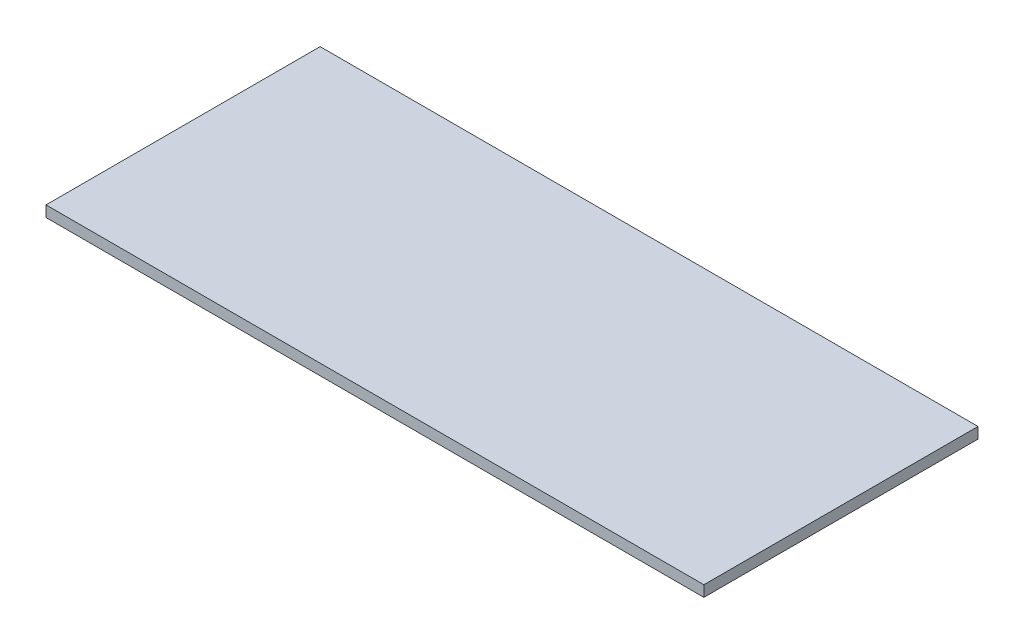
SolidWorks part; units mm, degrees
ref_plane "Front" through (0, 0, 0) normal (0, 0, 1) x (1, 0, 0)
ref_plane "Top" through (0, 0, 0) normal (0, 1, 0) x (1, 0, 0)
ref_plane "Right" through (0, 0, 0) normal (1, 0, 0) x (0, 0, -1)
sketch "Sketch1" plane through (0, 0, 0) normal (0, 1, 0) x (1, 0, 0)
  line L1 (-300, 125) -> (300, 125)
  line L2 (-300, 125) -> (-300, -125)
  line L3 (-300, -125) -> (300, -125)
  line L4 (300, 125) -> (300, -125)
  line L5 (-300, 125) -> (300, -125) construction
  line L6 (-300, -125) -> (300, 125) construction
  point P0 (0, 0)
  dimension "D1" = 250
  dimension "D2" = 600
extrude "Boss-Extrude1" add sketch "Sketch1" along normal blind 10
